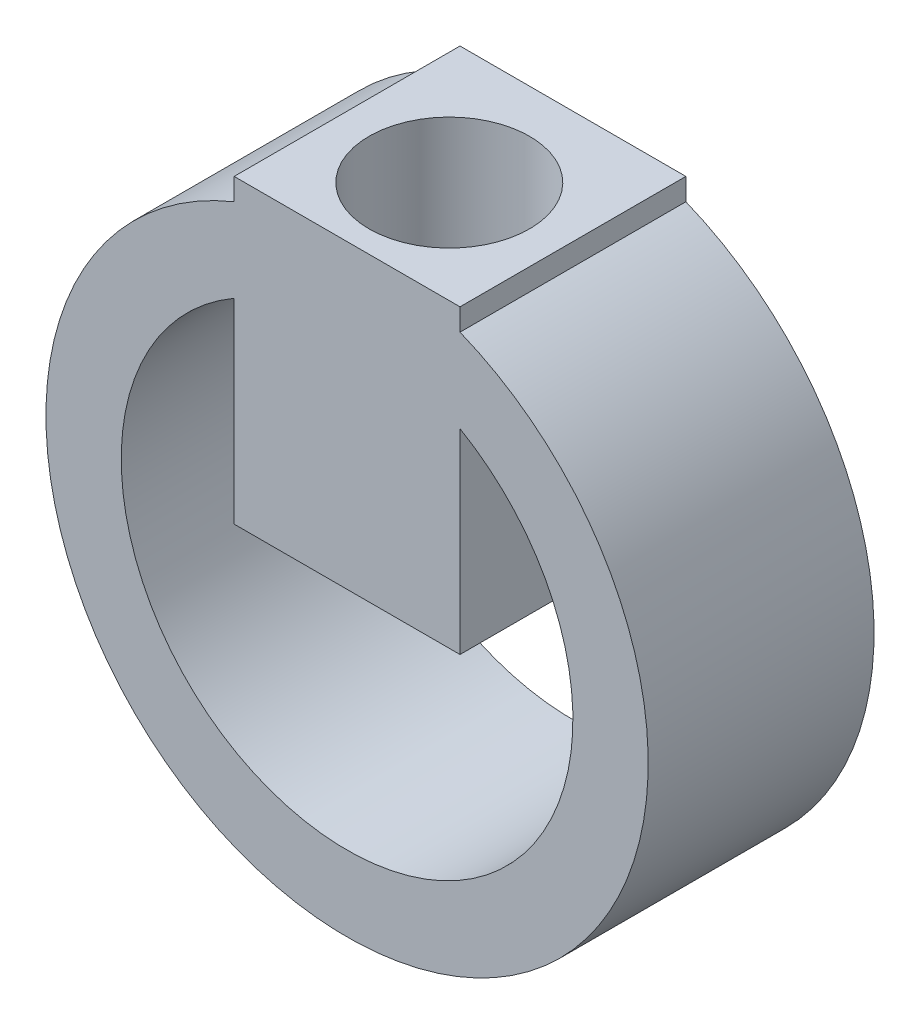
SolidWorks part; units mm, degrees
ref_plane "Front Plane" through (0, 0, 0) normal (0, 0, 1) x (1, 0, 0)
ref_plane "Top Plane" through (0, 0, 0) normal (0, 1, 0) x (1, 0, 0)
ref_plane "Right Plane" through (0, 0, 0) normal (1, 0, 0) x (0, 0, -1)
sketch "Sketch2" plane through (0, 0, 0) normal (0, 0, 1) x (1, 0, 0)
  circle A0 centre (0, 0) radius 25.4
  point P3 (0, 0)
  dimension "D1" = 50.8
extrude "Boss-Extrude1" add sketch "Sketch2" along normal blind 19.05
sketch "Sketch3" plane through (0, 0, 19.05) normal (0, 0, 1) x (1, 0, 0)
  circle A0 centre (0, 0) radius 19.05
  dimension "D1" = 38.1
extrude "Cut-Extrude1" cut sketch "Sketch3" against normal through all both and the other way through all
sketch "Sketch4" plane through (0, 0, 0) normal (0, 1, 0) x (1, 0, 0)
  line L1 (9.525, -19.05) -> (-9.525, -19.05)
  line L2 (9.525, -19.05) -> (9.525, 0)
  line L3 (9.525, 0) -> (-9.525, 0)
  line L4 (-9.525, -19.05) -> (-9.525, 0)
  line L5 (9.525, -19.05) -> (-9.525, 0) construction
  line L6 (9.525, 0) -> (-9.525, -19.05) construction
  point P0 (0, -9.525)
  point P5 (0, -9.525)
  dimension "D1" = 19.05
  dimension "D2" = 19.05
extrude "Boss-Extrude2" add sketch "Sketch4" along normal through all
sketch "Sketch7" plane through (0, 0, 0) normal (0, 1, 0) x (1, 0, 0)
  circle A0 centre (0, -10.4276) radius 6.7697
extrude "Cut-Extrude2" cut sketch "Sketch7" along normal through all
